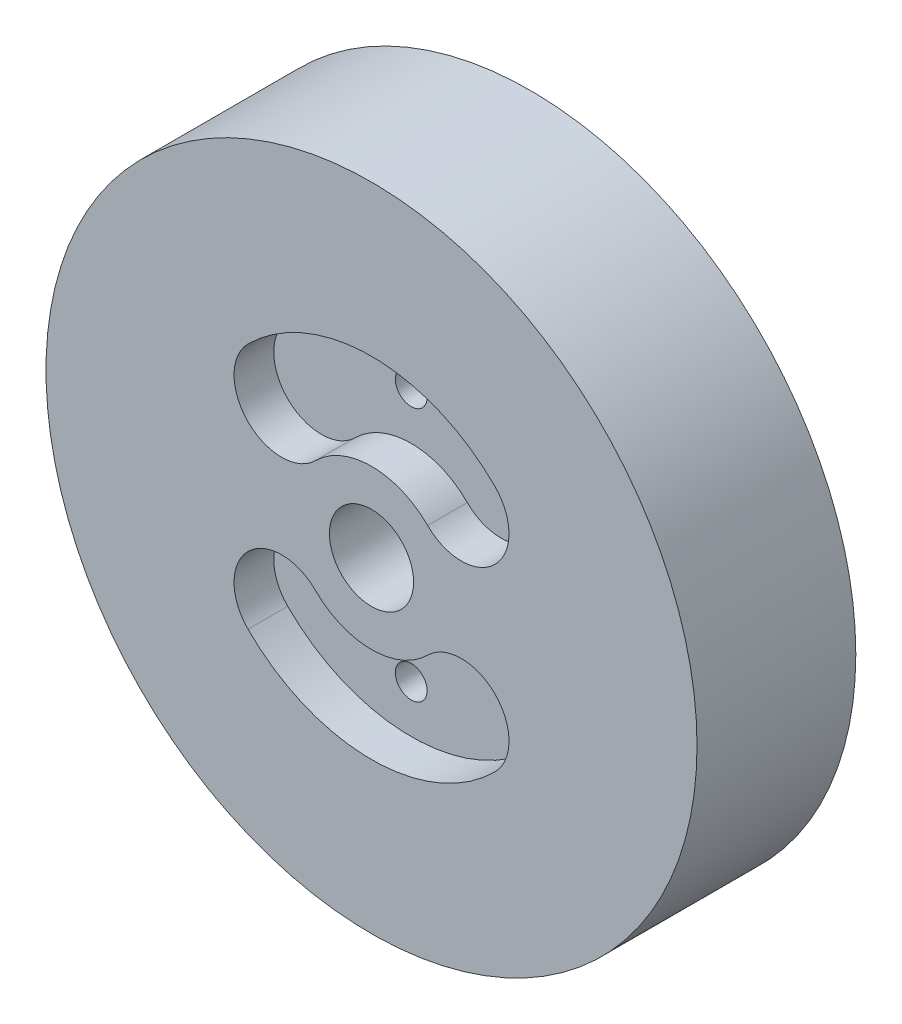
SolidWorks part; units mm, degrees
ref_plane "정면" through (0, 0, 0) normal (0, 0, 1) x (1, 0, 0)
ref_plane "윗면" through (0, 0, 0) normal (0, 1, 0) x (1, 0, 0)
ref_plane "우측면" through (0, 0, 0) normal (1, 0, 0) x (0, 0, -1)
sketch "스케치1" plane through (0, 0, 0) normal (0, 0, 1) x (1, 0, 0)
  circle A0 centre (0, 0) radius 20.5
  dimension "D1" = 41
extrude "보스-돌출1" add sketch "스케치1" along normal mid plane 10
hole_wizard "M5 여유 구멍1" positions "스케치2" profile "스케치3" hole size "M5" standard "KS" end condition through all
sketch "스케치2" plane through (0, 0, 5) normal (0, 0, 1) x (1, 0, 0)
  point P0 (0, 0)
sketch "스케치3" plane through (0, 0, 5) normal (1, 0, 0) x (0, -1, 0)
  line L0 (0, 0) -> (0, 10)
  line L1 (0, 10) -> (2.65, 10)
  line L2 (2.65, 10) -> (2.65, 0)
  line L5 (2.65, 0) -> (0, 0)
  line L11 (0, -6.35) -> (0, 107.95) construction
  dimension "관통 구멍 지름" = 5.3
  dimension "관통 구멍 깊이" = 10
hole_wizard "M5 여유 구멍2" positions "스케치4" profile "스케치5" hole size "M5" standard "KS"
sketch "스케치4" plane through (0, 0, -5) normal (0, 0, -1) x (-1, 0, 0)
  point P0 (12.5, 0)
  dimension "D1" = 12.5
sketch "스케치5" plane through (-12.5, 0, -5) normal (1, 0, 0) x (0, 1, 0)
  line L0 (0, 0) -> (0, 5)
  line L1 (0, 5) -> (2.65, 5)
  line L2 (2.65, 5) -> (2.65, 0)
  line L5 (2.65, 0) -> (0, 0)
  line L10 (0, 5) -> (-2.65, 5) construction
  line L11 (0, -6.35) -> (0, 107.95) construction
  dimension "구멍 지름" = 5.3
  dimension "구멍 깊이" = 5
  dimension "드릴 각도" = 180
mirror "대칭 복사1" about plane through (0, 0, 0) normal (1, 0, 0) of "M5 여유 구멍2"
sketch "스케치6" plane through (0, 0, 5) normal (0, 0, 1) x (1, 0, 0)
  line L0 (0, 8) -> (0, 0) construction
  line L1 (-5.6569, 5.6569) -> (0, 0) construction
  line L2 (0, 0) -> (5.6569, 5.6569) construction
  arc A0 (-5.6569, 5.6569) -> (5.6569, 5.6569) centre (0, 0) cw construction
  arc A1 (7.7782, 7.7782) -> (-7.7782, 7.7782) centre (0, 0) ccw
  arc A2 (3.5355, 3.5355) -> (-3.5355, 3.5355) centre (0, 0) ccw
  arc A3 (3.5355, 3.5355) -> (7.7782, 7.7782) centre (5.6569, 5.6569) ccw
  arc A4 (-7.7782, 7.7782) -> (-3.5355, 3.5355) centre (-5.6569, 5.6569) ccw
  point P4 (0, 8)
  dimension "D1" = 5
  dimension "D2" = 11
  dimension "D3" = 90
extrude "컷-돌출1" cut sketch "스케치6" against normal blind 2.5
hole_wizard "Ø2.0 (2) 지름 구멍1" positions "스케치7" profile "스케치8" hole size "Ø2.0" standard "KS" end condition through all
sketch "스케치7" plane through (0, 0, 2.5) normal (0, 0, 1) x (1, 0, 0)
  point P0 (0, 8)
sketch "스케치8" plane through (0, 8, 2.5) normal (1, 0, 0) x (0, -1, 0)
  line L0 (0, 0) -> (0, 7.5)
  line L1 (0, 7.5) -> (1, 7.5)
  line L2 (1, 7.5) -> (1, 0)
  line L5 (1, 0) -> (0, 0)
  line L11 (0, -6.35) -> (0, 107.95) construction
  dimension "관통 구멍 지름" = 2
  dimension "관통 구멍 깊이" = 7.5
pattern_circular "원형 패턴1" count 2 over 360 about axis through (0, 0, 0) along (0, 0, 1) of "Ø2.0 (2) 지름 구멍1", "컷-돌출1"
